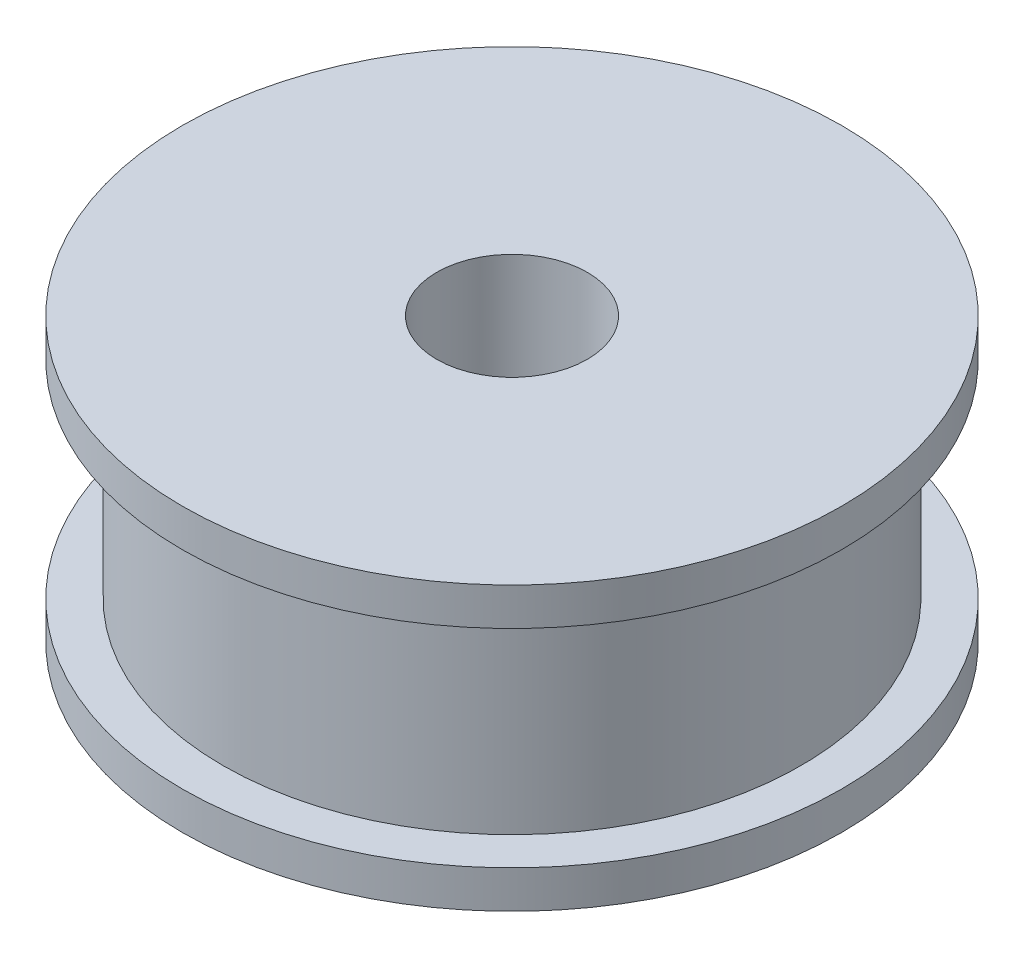
SolidWorks part; units mm, degrees
ref_plane "前视基准面" through (0, 0, 0) normal (0, 0, 1) x (1, 0, 0)
ref_plane "上视基准面" through (0, 0, 0) normal (0, 1, 0) x (1, 0, 0)
ref_plane "右视基准面" through (0, 0, 0) normal (1, 0, 0) x (0, 0, -1)
other "Configuration Table"
sketch "草图1" plane through (0, 0, 0) normal (0, 1, 0) x (1, 0, 0)
  circle A0 centre (0, 0) radius 4
  circle A1 centre (0, 0) radius 15.345
  dimension "D1" = 8
  dimension "D2" = 30.69
extrude "凸台-拉伸1" add sketch "草图1" along normal blind 11
sketch "草图2" plane through (0, 11, 0) normal (0, 1, 0) x (1, 0, 0)
  circle A0 centre (0, 0) radius 4 construction
  circle A1 centre (0, 0) radius 4
  circle A2 centre (0, 0) radius 17.5
  dimension "D1" = 35
extrude "凸台-拉伸2" add sketch "草图2" along normal blind 2
sketch "草图3" plane through (0, 0, 0) normal (0, -1, 0) x (1, 0, 0)
  circle A0 centre (0, 0) radius 4 construction
  circle A1 centre (0, 0) radius 4
  circle A2 centre (0, 0) radius 17.5 construction
  circle A3 centre (0, 0) radius 17.5
extrude "凸台-拉伸3" add sketch "草图3" along normal blind 2
